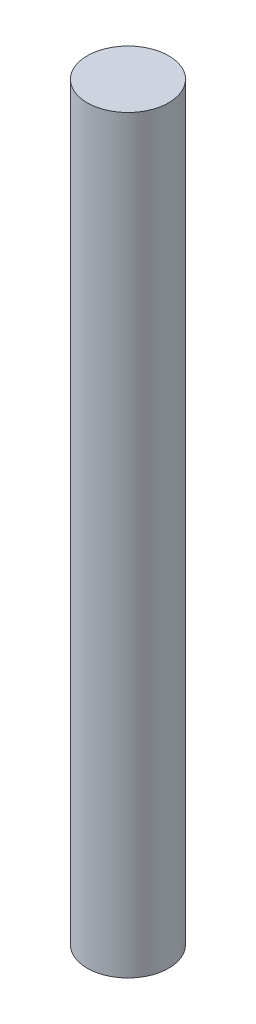
SolidWorks part; units mm, degrees
ref_plane "前视基准面" through (0, 0, 0) normal (0, 0, 1) x (1, 0, 0)
ref_plane "上视基准面" through (0, 0, 0) normal (0, 1, 0) x (1, 0, 0)
ref_plane "右视基准面" through (0, 0, 0) normal (1, 0, 0) x (0, 0, -1)
other "Configuration Table"
sketch "草图1" plane through (0, 0, 0) normal (0, 1, 0) x (1, 0, 0)
  circle A0 centre (0, 0) radius 0.5
  dimension "D1" = 1
extrude "凸台-拉伸1" add sketch "草图1" along normal blind 9.2
